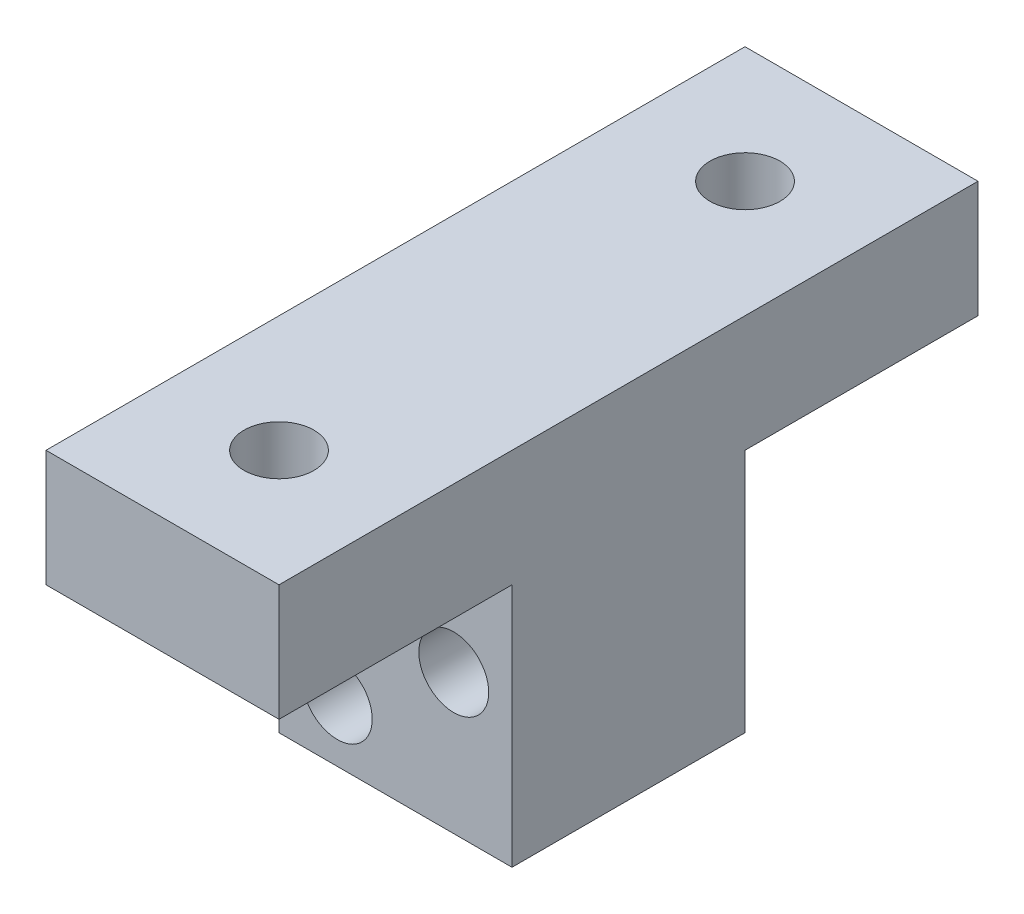
SolidWorks part; units mm, degrees
ref_plane "前视基准面" through (0, 0, 0) normal (0, 0, 1) x (1, 0, 0)
ref_plane "上视基准面" through (0, 0, 0) normal (0, 1, 0) x (1, 0, 0)
ref_plane "右视基准面" through (0, 0, 0) normal (1, 0, 0) x (0, 0, -1)
sketch "草图1" plane through (0, 0, 0) normal (0, 0, 1) x (1, 0, 0)
  line L1 (5, -7.75) -> (-5, -7.75)
  line L2 (5, -7.75) -> (5, 7.75)
  line L3 (5, 7.75) -> (-5, 7.75)
  line L4 (-5, -7.75) -> (-5, 7.75)
  line L5 (5, -7.75) -> (-5, 7.75) construction
  line L6 (5, 7.75) -> (-5, -7.75) construction
  point P0 (0, 0)
  dimension "D1" = 15.5
  dimension "D2" = 10
extrude "凸台-拉伸1" add sketch "草图1" along normal blind 10
sketch "草图2" plane through (0, 7.75, 0) normal (0, 1, 0) x (1, 0, 0)
  line L1 (-5, -10) -> (5, -10)
  line L2 (-5, -10) -> (-5, -20)
  line L3 (-5, -20) -> (5, -20)
  line L4 (5, -10) -> (5, -20)
  line L5 (-5, -10) -> (5, -20) construction
  line L6 (-5, -20) -> (5, -10) construction
  line L7 (-5, 0) -> (5, 0)
  line L8 (-5, 0) -> (-5, 10)
  line L9 (-5, 10) -> (5, 10)
  line L10 (5, 0) -> (5, 10)
  line L11 (-5, 0) -> (5, 10) construction
  line L12 (-5, 10) -> (5, 0) construction
  point P4 (0, -15)
  point P10 (0, 5)
  dimension "D1" = 10
  dimension "D2" = 10
extrude "凸台-拉伸2" add sketch "草图2" against normal blind 5
sketch "草图3" plane through (0, 2.75, 0) normal (0, -1, 0) x (1, 0, 0)
  line L0 (-5, 20) -> (5, 20) construction
  line L1 (5, 20) -> (5, 10) construction
  line L2 (5, -10) -> (-5, -10) construction
  line L3 (5, 0) -> (5, -10) construction
  circle A0 centre (0, -5) radius 1.5
  circle A1 centre (0, 15) radius 1.5
  point P10 (0, -10)
  dimension "D1" = 3
  dimension "D2" = 3
  dimension "D3" = 5
  dimension "D4" = 5
  dimension "D5" = 5
  dimension "D6" = 5
extrude "切除-拉伸1" cut sketch "草图3" against normal blind 5
sketch "草图4" plane through (0, 0, 10) normal (0, 0, 1) x (1, 0, 0)
  line L0 (-5, 2.75) -> (-5, -7.75) construction
  line L1 (-5, -7.75) -> (5, -7.75) construction
  line L3 (5, -7.75) -> (5, 2.75) construction
  circle A0 centre (-2.5, -5.25) radius 1.5
  circle A1 centre (2.5, -1.75) radius 1.5
  dimension "D1" = 3
  dimension "D2" = 3
  dimension "D4" = 2.5
  dimension "D3" = 2.5
  dimension "D5" = 6
  dimension "D6" = 2.5
extrude "切除-拉伸2" cut sketch "草图4" against normal blind 10
